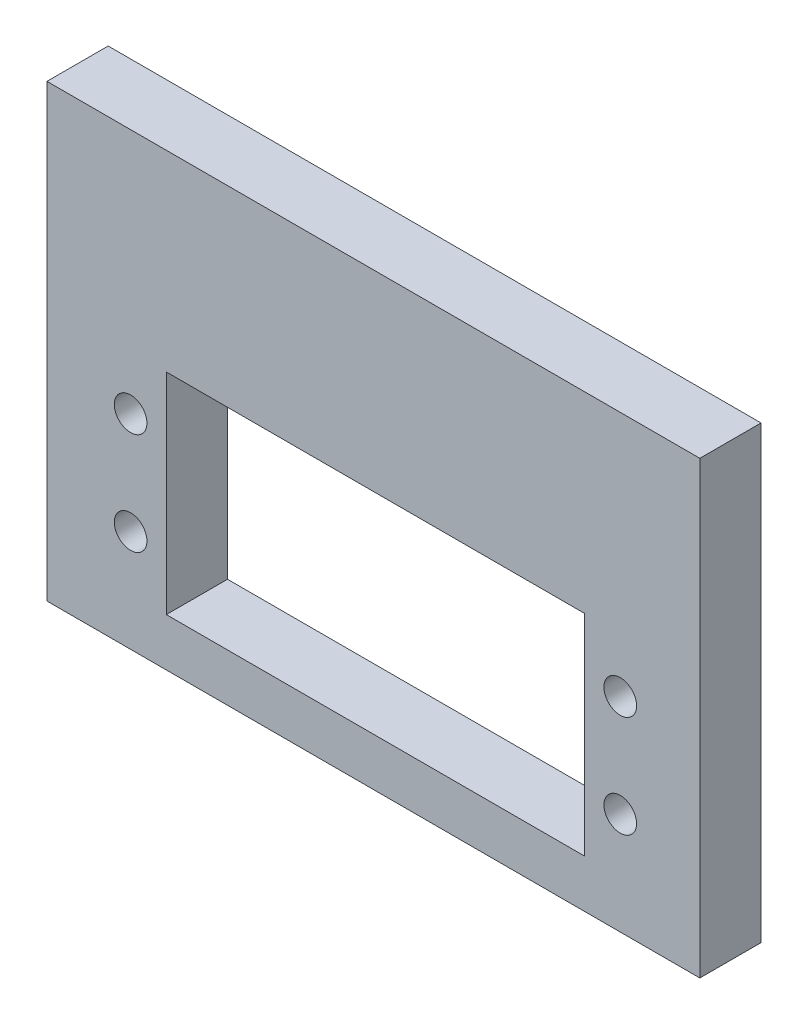
SolidWorks part; units mm, degrees
ref_plane "Front Plane" through (0, 0, 0) normal (0, 0, 1) x (1, 0, 0)
ref_plane "Top Plane" through (0, 0, 0) normal (0, 1, 0) x (1, 0, 0)
ref_plane "Right Plane" through (0, 0, 0) normal (1, 0, 0) x (0, 0, -1)
sketch "Sketch1" plane through (0, 0, 0) normal (0, 0, 1) x (1, 0, 0)
  line L0 (-22, 4.8797) -> (42, 4.8797)
  line L1 (42, 4.8797) -> (42, 49)
  line L2 (42, 49) -> (-22, 49)
  line L3 (-22, 49) -> (-22, 4.8797)
  line L4 (-10.3, 9.5797) -> (30.7, 9.5797)
  line L5 (30.7, 9.5797) -> (30.7, 30.1797)
  line L6 (30.7, 30.1797) -> (-10.3, 30.1797)
  line L7 (-10.3, 30.1797) -> (-10.3, 9.5797)
  circle A0 centre (-13.8, 14.8797) radius 1.6
  circle A1 centre (-13.8, 24.8797) radius 1.6
  circle A2 centre (34.2, 14.8797) radius 1.6
  circle A3 centre (34.2, 24.8797) radius 1.6
extrude "Boss-Extrude1" add sketch "Sketch1" along normal blind 6
